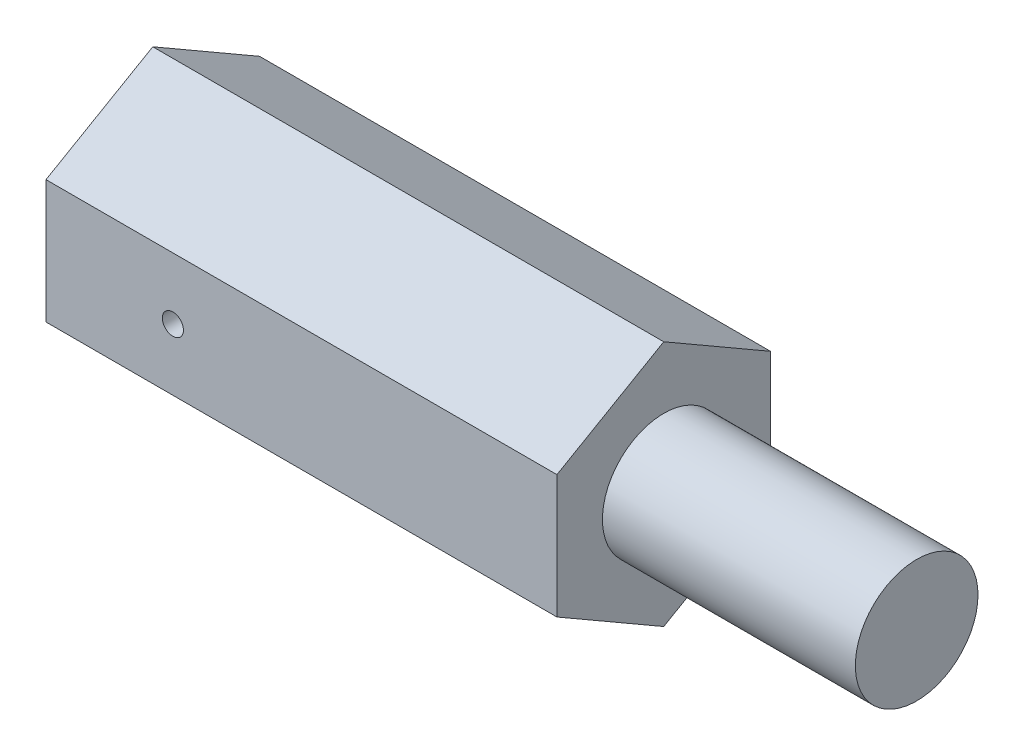
SolidWorks part; units mm, degrees
ref_plane "Piano frontale" through (0, 0, 0) normal (0, 0, 1) x (1, 0, 0)
ref_plane "Piano superiore" through (0, 0, 0) normal (0, 1, 0) x (1, 0, 0)
ref_plane "Piano destro" through (0, 0, 0) normal (1, 0, 0) x (0, 0, -1)
sketch "Schizzo1" plane through (0, 0, 0) normal (1, 0, 0) x (0, 0, -1)
  line L1 (0, 2.9156) -> (-2.525, 1.4578)
  line L2 (-2.525, 1.4578) -> (-2.525, -1.4578)
  line L3 (-2.525, -1.4578) -> (0, -2.9156)
  line L4 (0, -2.9156) -> (2.525, -1.4578)
  line L5 (2.525, -1.4578) -> (2.525, 1.4578)
  line L6 (2.525, 1.4578) -> (0, 2.9156)
  circle A0 centre (0, 0) radius 2.9156 construction
  dimension "D1" = 5.05
extrude "Estrusione-Estrusione1" add sketch "Schizzo1" along normal blind 12.08
sketch "Schizzo2" plane through (12.08, 0, 0) normal (1, 0, 0) x (0, 0, -1)
  circle A0 centre (0, 0) radius 1.45
  dimension "D1" = 2.9
extrude "Estrusione-Estrusione2" add sketch "Schizzo2" along normal blind 5.98
cosmetic thread "Filettatura cosmetica1" parameters "D2"=2.439
hole_wizard "Foro filettato M3x0.5-1" positions "Schizzo4" profile "Schizzo3" tap size "M3x0.5" standard "Ansi Metric"
sketch "Schizzo4" plane through (0, 0, 0) normal (-1, 0, 0) x (0, 0, 1)
  point P0 (0, 0)
sketch "Schizzo3" plane through (0, 0, 0) normal (0, 1, 0) x (0, 0, 1)
  line L0 (0, 0) -> (0, 8.7511)
  line L1 (0, 8.7511) -> (1.25, 8)
  line L2 (1.25, 8) -> (1.25, 0.75)
  line L3 (1.25, 0.75) -> (2, 0)
  line L5 (2, 0) -> (0, 0)
  line L6 (-1.25, 0.75) -> (-2, 0) construction
  line L10 (0, 8.7511) -> (-1.25, 8) construction
  line L11 (0, -6.35) -> (0, 107.95) construction
  dimension "Tap Drill Dia." = 2.5
  dimension "Tap Drill Depth" = 8
  dimension "Near C'Sink Dia." = 4
  dimension "Near C'Sink Angle" = 90
  dimension "Drill Angle" = 118
cosmetic thread "Filettatura del foro2" parameters "D1"=7, "D2"=3
sketch "Schizzo5" plane through (0, 0, 2.525) normal (0, 0, 1) x (1, 0, 0)
  line L0 (0, 1.4578) -> (0, -1.4578) construction
  circle A0 centre (3, 0) radius 0.25
  point P4 (0, 0)
  dimension "D1" = 0.5
  dimension "D2" = 3
extrude "Taglio-Estrusione1" cut sketch "Schizzo5" against normal up to next
sketch "Schizzo6" plane through (0, 0, -2.525) normal (0, 0, -1) x (-1, 0, 0)
  circle A0 centre (-3, 0) radius 1
  dimension "D1" = 2
extrude "Taglio-Estrusione2" cut sketch "Schizzo6" against normal up to next
